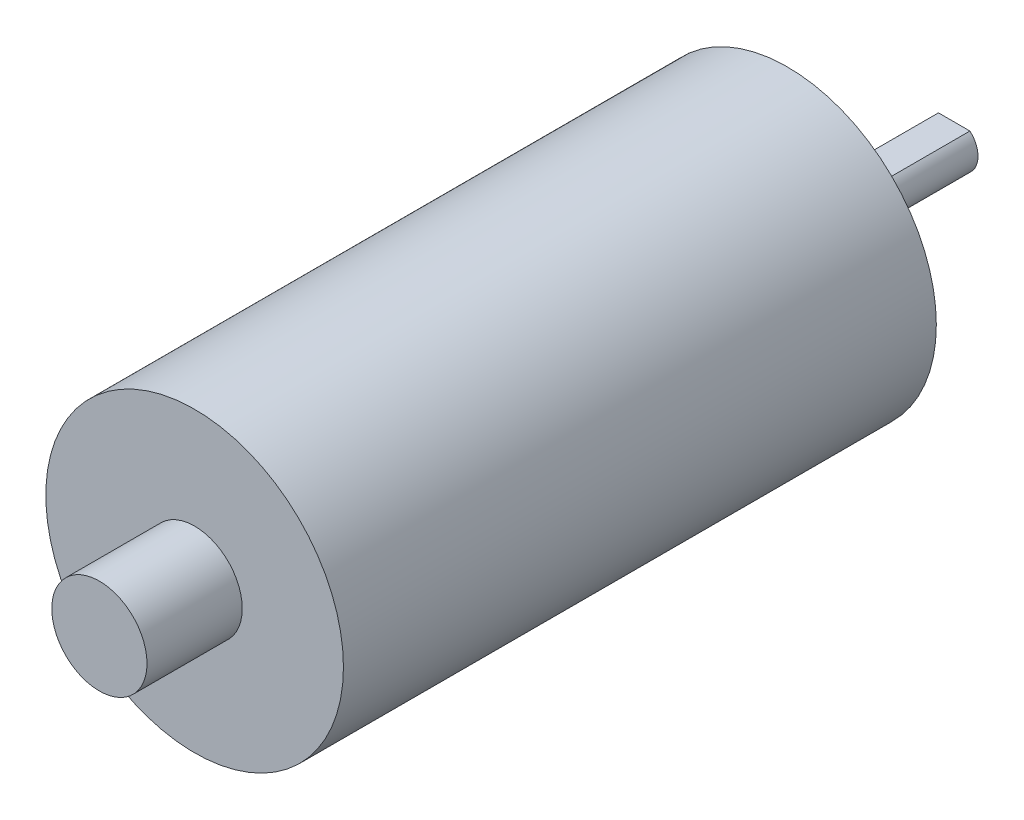
SolidWorks part; units mm, degrees
ref_plane "前视基准面" through (0, 0, 0) normal (0, 0, 1) x (1, 0, 0)
ref_plane "上视基准面" through (0, 0, 0) normal (0, 1, 0) x (1, 0, 0)
ref_plane "右视基准面" through (0, 0, 0) normal (1, 0, 0) x (0, 0, -1)
sketch "草图1" plane through (0, 0, 0) normal (0, 0, 1) x (1, 0, 0)
  circle A0 centre (0, 0) radius 12.5
  dimension "D1" = 25
extrude "凸台-拉伸1" add sketch "草图1" along normal blind 49.8
sketch "草图2" plane through (0, 0, 0) normal (0, 0, -1) x (-1, 0, 0)
  circle A0 centre (0, 0) radius 3.5
  dimension "D1" = 7
extrude "凸台-拉伸2" add sketch "草图2" along normal blind 2.5
sketch "草图3" plane through (0, 0, -2.5) normal (0, 0, -1) x (-1, 0, 0)
  circle A0 centre (0, 0) radius 2
  dimension "D1" = 4
extrude "凸台-拉伸3" add sketch "草图3" along normal blind 11.5
sketch "草图4" plane through (0, 0, -14) normal (0, 0, -1) x (-1, 0, 0)
  line L1 (0, -2) -> (-2.2814, -2)
  line L2 (0, -2) -> (0, 1.5)
  line L3 (0, 1.5) -> (-2.2814, 1.5)
  line L4 (-2.2814, -2) -> (-2.2814, 1.5)
  line L5 (0, 1.5) -> (2.4998, 1.5)
  line L6 (0, 1.5) -> (0, -2)
  line L7 (0, -2) -> (2.4998, -2)
  line L8 (2.4998, 1.5) -> (2.4998, -2)
  circle A0 centre (0, 0) radius 2
  circle M2 centre (0, 0) radius 2
  dimension "D1" = 3.5
extrude "切除-拉伸1" cut sketch "草图4" against normal blind 9 contours L3 L5 M2
sketch "草图5" plane through (0, 0, 0) normal (0, 0, -1) x (-1, 0, 0)
  line L0 (0, 0) -> (0, -5.0118) construction
  circle A0 centre (8.5, 0) radius 1.5
  circle A1 centre (-8.5, 0) radius 1.5
  dimension "D1" = 3
  dimension "D2" = 8.5
extrude "切除-拉伸2" cut sketch "草图5" against normal blind 3
sketch "草图6" plane through (0, 0, 49.8) normal (0, 0, 1) x (1, 0, 0)
  circle A0 centre (0, 0) radius 4
  dimension "D1" = 8
extrude "凸台-拉伸4" add sketch "草图6" along normal blind 8
